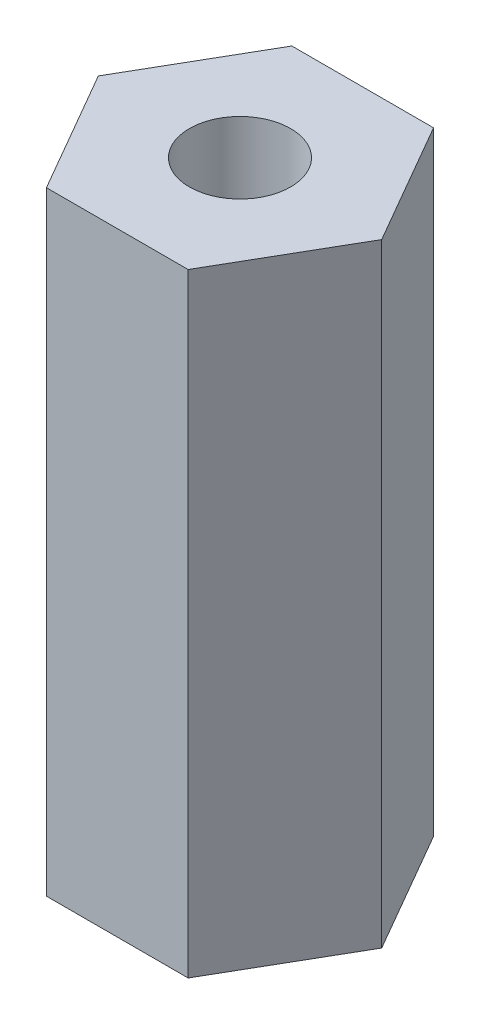
SolidWorks part; units mm, degrees
ref_plane "前视基准面" through (0, 0, 0) normal (0, 0, 1) x (1, 0, 0)
ref_plane "上视基准面" through (0, 0, 0) normal (0, 1, 0) x (1, 0, 0)
ref_plane "右视基准面" through (0, 0, 0) normal (1, 0, 0) x (0, 0, -1)
sketch "草图1" plane through (0, 0, 0) normal (0, 1, 0) x (1, 0, 0)
  line L0 (4.6188, 0) -> (2.3094, -4)
  line L1 (2.3094, -4) -> (-2.3094, -4)
  line L2 (-2.3094, -4) -> (-4.6188, 0)
  line L3 (-4.6188, 0) -> (-2.3094, 4)
  line L4 (-2.3094, 4) -> (2.3094, 4)
  line L5 (2.3094, 4) -> (4.6188, 0)
extrude "凸台-拉伸1" add sketch "草图1" along normal blind 20
sketch "草图2" plane through (0, 0, 0) normal (0, 1, 0) x (1, 0, 0)
  circle A0 centre (0, 0) radius 1.65
extrude "切除-拉伸1" cut sketch "草图2" along normal blind 6
ref_plane "基准面1" through (0, 20, 0) normal (0, 1, 0) x (1, 0, 0)
sketch "草图3" plane through (0, 20, 0) normal (0, 1, 0) x (1, 0, 0)
  circle A0 centre (0, 0) radius 1.65
extrude "切除-拉伸2" cut sketch "草图3" against normal blind 6
